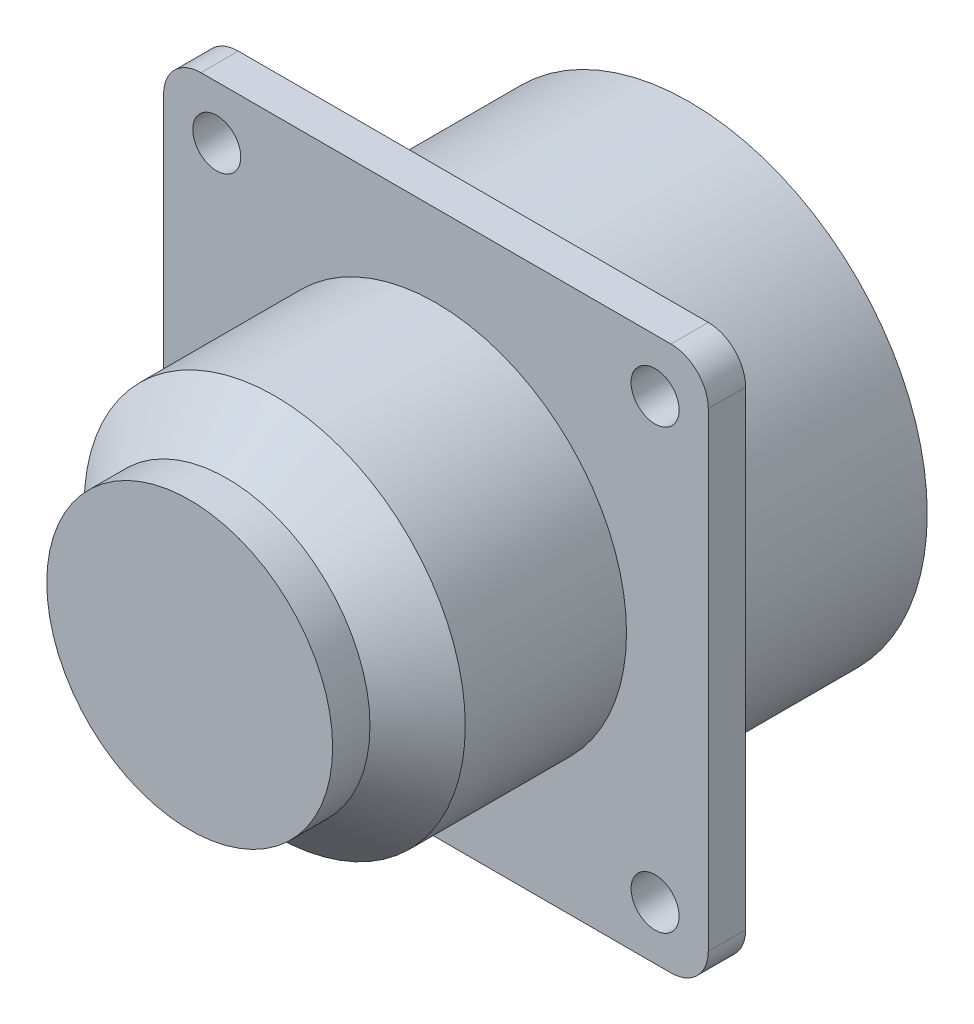
SolidWorks part; units mm, degrees
ref_plane "front" through (0, 0, 0) normal (0, 0, 1) x (1, 0, 0)
ref_plane "top" through (0, 0, 0) normal (0, 1, 0) x (1, 0, 0)
ref_plane "right" through (0, 0, 0) normal (1, 0, 0) x (0, 0, -1)
sketch "Sketch1" plane through (0, 0, 0) normal (1, 0, 0) x (0, 0, -1)
  line L0 (0, 0) -> (-57.5873, 0) construction
  line L1 (-2.4892, 25.4) -> (0, 25.4)
  line L2 (0, 25.4) -> (0, 15.8496)
  line L3 (0, 15.8496) -> (14.4018, 15.8496)
  line L4 (14.4018, 15.8496) -> (14.4018, 0)
  line L5 (-2.4892, 25.4) -> (-2.4892, 12.7)
  line L6 (-2.4892, 12.7) -> (-13.2334, 12.7)
  line L7 (-13.2334, 12.7) -> (-16.4084, 9.525)
  line L8 (-16.4084, 9.525) -> (-18.8976, 9.525)
  line L9 (-18.8976, 9.525) -> (-18.8976, 0)
  line L10 (-18.8976, 0) -> (14.4018, 0)
  dimension "D1" = 2.4892
  dimension "D2" = 31.6992
  dimension "D3" = 14.4018
  dimension "D4" = 33.2994
  dimension "D5" = 25.4
  dimension "D6" = 19.05
  dimension "D7" = 45
  dimension "D8" = 2.4892
  dimension "D9" = 50.8
revolve "Revolve1" add sketch "Sketch1" angle 360 about L0
sketch "Sketch2" plane through (0, 0, 0) normal (0, 0, 1) x (1, 0, 0)
  line L1 (-15.6591, 18.1483) -> (15.6591, 18.1483)
  line L2 (-18.1483, 15.6591) -> (-18.1483, -15.6591)
  line L3 (-15.6591, -18.1483) -> (15.6591, -18.1483)
  line L4 (18.1483, 15.6591) -> (18.1483, -15.6591)
  arc A0 (15.6591, 18.1483) -> (18.1483, 15.6591) centre (15.6591, 15.6591) cw
  arc A1 (-15.6591, 18.1483) -> (-18.1483, 15.6591) centre (-15.6591, 15.6591) ccw
  arc A2 (-18.1483, -15.6591) -> (-15.6591, -18.1483) centre (-15.6591, -15.6591) ccw
  arc A3 (15.6591, -18.1483) -> (18.1483, -15.6591) centre (15.6591, -15.6591) ccw
  point P4 (0, 18.1483)
  point P5 (18.1483, 0)
  dimension "D2" = 2.4892
  dimension "D1" = 36.2966
extrude "Cut-Extrude2" cut sketch "Sketch2" along normal through all flip side to cut
sketch "Sketch4" plane through (0, 0, 0) normal (0, 0, 1) x (1, 0, 0)
  line L0 (0, 0) -> (4.7838, 0) construction
  line L1 (0, 0) -> (0, 5.3659) construction
  circle A0 centre (-14.605, 14.605) radius 1.6002
  circle A1 centre (14.605, 14.605) radius 1.6002
  circle A2 centre (-14.605, -14.605) radius 1.6002
  circle A3 centre (14.605, -14.605) radius 1.6002
  dimension "D3" = 3.2004
  dimension "D1" = 29.21
  dimension "D2" = 29.21
extrude "Cut-Extrude4" cut sketch "Sketch4" along normal through all
